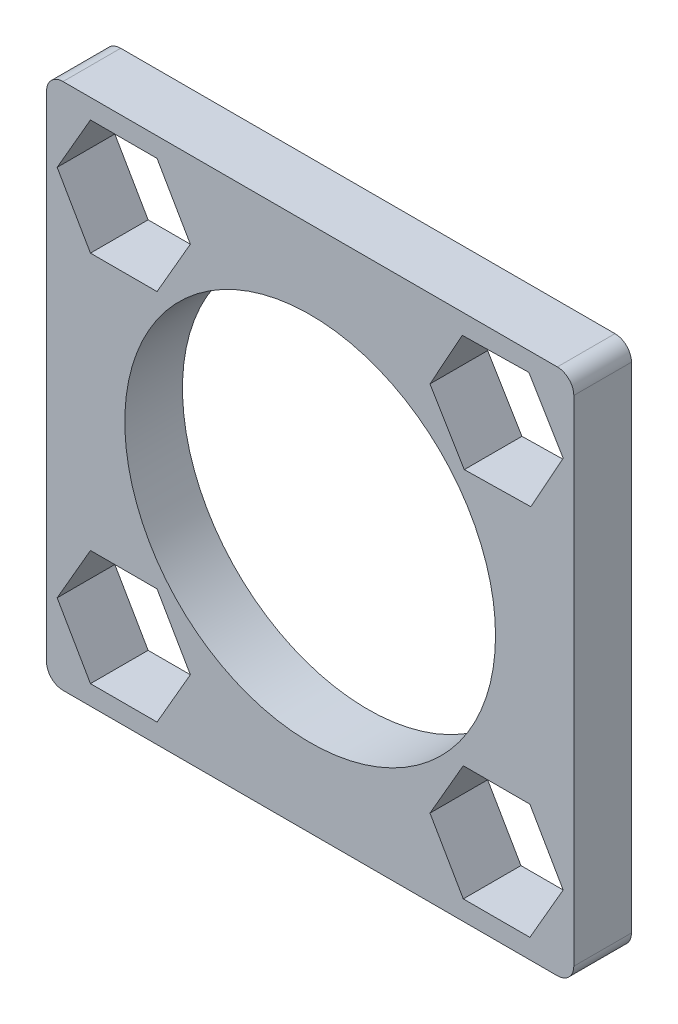
SolidWorks part; units mm, degrees
ref_plane "Front" through (0, 0, 0) normal (0, 0, 1) x (1, 0, 0)
ref_plane "Top" through (0, 0, 0) normal (0, 1, 0) x (1, 0, 0)
ref_plane "Right" through (0, 0, 0) normal (1, 0, 0) x (0, 0, -1)
sketch "Эскиз1" plane through (0, 0, 0) normal (0, 0, 1) x (1, 0, 0)
  line L1 (-15, 16) -> (15, 16)
  line L2 (-16, 15) -> (-16, -15)
  line L3 (-15, -16) -> (15, -16)
  line L4 (16, 15) -> (16, -15)
  line L5 (-16, 16) -> (16, -16) construction
  line L6 (-16, -16) -> (16, 16) construction
  line L7 (-7.2723, 11.3137) -> (-9.293, 14.8137)
  line L8 (-9.293, 14.8137) -> (-13.3344, 14.8137)
  line L9 (-13.3344, 14.8137) -> (-15.3552, 11.3137)
  line L10 (-15.3552, 11.3137) -> (-13.3344, 7.8137)
  line L11 (-13.3344, 7.8137) -> (-9.293, 7.8137)
  line L12 (-9.293, 7.8137) -> (-7.2723, 11.3137)
  line L13 (7.2729, 11.2439) -> (9.3538, 7.7793)
  line L14 (9.3538, 7.7793) -> (13.3946, 7.8491)
  line L15 (13.3946, 7.8491) -> (15.3546, 11.3835)
  line L16 (15.3546, 11.3835) -> (13.2737, 14.8481)
  line L17 (13.2737, 14.8481) -> (9.2328, 14.7783)
  line L18 (9.2328, 14.7783) -> (7.2729, 11.2439)
  line L19 (-7.2723, -11.3137) -> (-9.293, -7.8137)
  line L20 (-9.293, -7.8137) -> (-13.3344, -7.8137)
  line L21 (-13.3344, -7.8137) -> (-15.3552, -11.3137)
  line L22 (-15.3552, -11.3137) -> (-13.3344, -14.8137)
  line L23 (-13.3344, -14.8137) -> (-9.293, -14.8137)
  line L24 (-9.293, -14.8137) -> (-7.2723, -11.3137)
  line L25 (15.3552, -11.3137) -> (13.3344, -7.8137)
  line L26 (13.3344, -7.8137) -> (9.293, -7.8137)
  line L27 (9.293, -7.8137) -> (7.2723, -11.3137)
  line L28 (7.2723, -11.3137) -> (9.293, -14.8137)
  line L29 (9.293, -14.8137) -> (13.3344, -14.8137)
  line L30 (13.3344, -14.8137) -> (15.3552, -11.3137)
  circle A0 centre (0, 0) radius 11.25
  circle A1 centre (0, 0) radius 16 construction
  circle A2 centre (-11.3137, 11.3137) radius 3.5 construction
  circle A3 centre (11.3137, 11.3137) radius 3.5 construction
  circle A4 centre (-11.3137, -11.3137) radius 3.5 construction
  circle A5 centre (11.3137, -11.3137) radius 3.5 construction
  arc A6 (-16, -15) -> (-15, -16) centre (-15, -15) ccw
  arc A7 (15, -16) -> (16, -15) centre (15, -15) ccw
  arc A8 (15, 16) -> (16, 15) centre (15, 15) cw
  arc A9 (-15, 16) -> (-16, 15) centre (-15, 15) ccw
  point P0 (0, 0)
  dimension "D3" = 22.5
  dimension "D4" = 32
  dimension "D5" = 1
  dimension "D1" = 32
  dimension "D2" = 32
extrude "Бобышка-Вытянуть2" add sketch "Эскиз1" along normal blind 3.5
